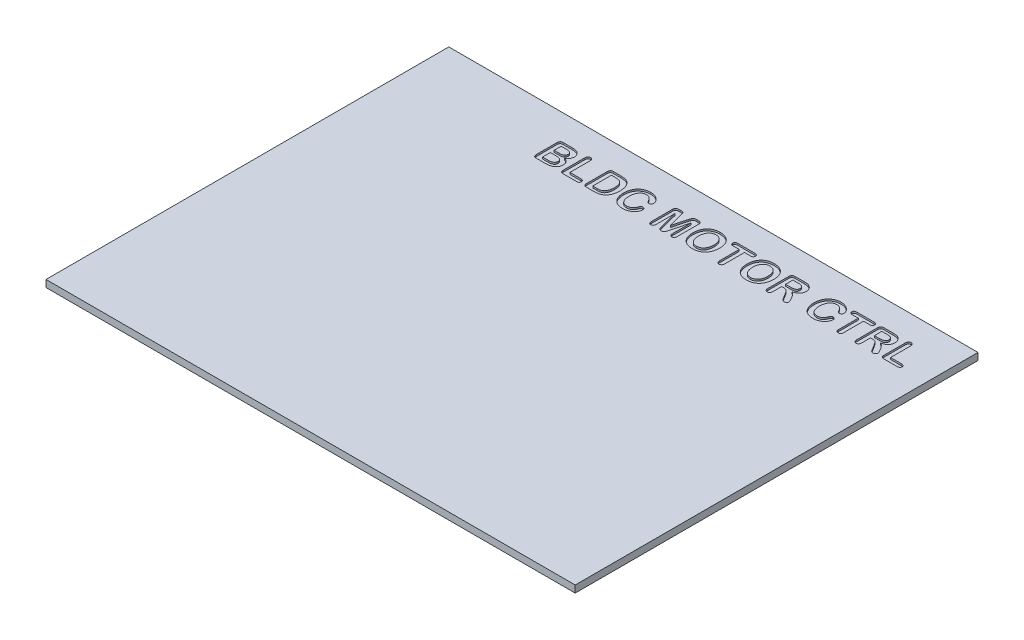
SolidWorks part; units mm, degrees
ref_plane "Front Plane" through (0, 0, 0) normal (0, 0, 1) x (1, 0, 0)
ref_plane "Top Plane" through (0, 0, 0) normal (0, 1, 0) x (1, 0, 0)
ref_plane "Right Plane" through (0, 0, 0) normal (1, 0, 0) x (0, 0, -1)
sketch "Sketch1" plane through (0, 0, 0) normal (0, 1, 0) x (1, 0, 0)
  line L5 (-75.35, 57.35) -> (75.35, 57.35)
  line L6 (-75.35, 57.35) -> (-75.35, -57.35)
  line L7 (-75.35, -57.35) -> (75.35, -57.35)
  line L8 (75.35, 57.35) -> (75.35, -57.35)
  line L9 (-75.35, 57.35) -> (75.35, -57.35) construction
  line L10 (-75.35, -57.35) -> (75.35, 57.35) construction
  point P0 (0, 0)
  dimension "D1" = 150.7
  dimension "D2" = 114.7
extrude "Boss-Extrude1" add sketch "Sketch1" along normal blind 2
sketch "Sketch2" plane through (0, 2, 0) normal (0, 1, 0) x (1, 0, 0)
  line L0 (-75.35, 57.35) -> (-75.35, -57.35) construction
  line L1 (-75.35, 50.35) -> (68.35, 50.35) construction
  line L2 (-75.35, 50.35) -> (-75.35, 42.35) construction
  line L3 (-75.35, 42.35) -> (68.35, 42.35) construction
  line L4 (68.35, 50.35) -> (68.35, 42.35) construction
  line L5 (75.35, 57.35) -> (-75.35, 57.35) construction
  line L6 (75.35, -57.35) -> (75.35, 57.35) construction
  text T0 "BLDC MOTOR CTRL" font "Arial Rounded MT Bold" height 8
  dimension "D1" = 7
  dimension "D2" = 7
  dimension "D3" = 8
extrude "Cut-Extrude1" cut sketch "Sketch2" against normal blind 0.5
